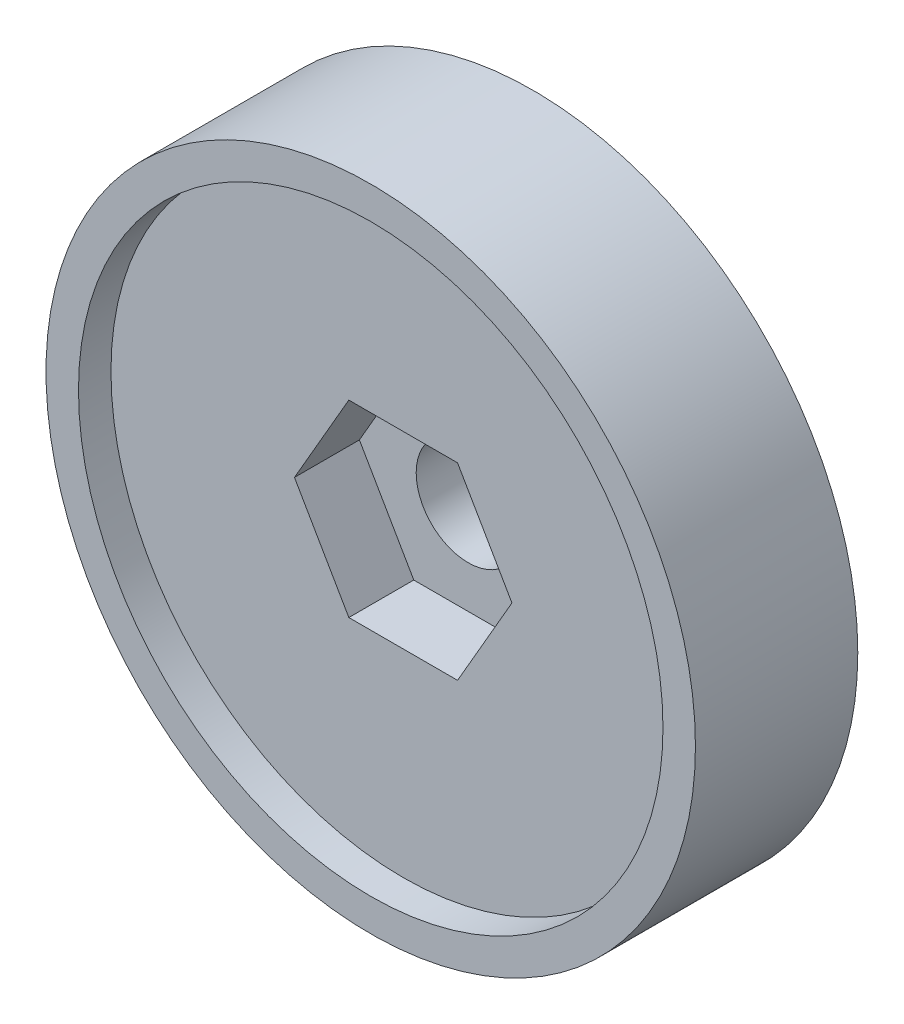
SolidWorks part; units mm, degrees
ref_plane "Front Plane" through (0, 0, 0) normal (0, 0, 1) x (1, 0, 0)
ref_plane "Top Plane" through (0, 0, 0) normal (0, 1, 0) x (1, 0, 0)
ref_plane "Right Plane" through (0, 0, 0) normal (1, 0, 0) x (0, 0, -1)
sketch "Sketch1" plane through (0, 0, 0) normal (0, 0, 1) x (1, 0, 0)
  circle A0 centre (-85, 80) radius 10
  circle A1 centre (-85, 80) radius 1.5 construction
  circle A2 centre (-85, 80) radius 1.5
  dimension "D1" = 20
extrude "Boss-Extrude1" add sketch "Sketch1" along normal blind 2
sketch "Sketch2" plane through (0, 0, 2) normal (0, 0, 1) x (1, 0, 0)
  circle A0 centre (-85, 80) radius 10
  circle A1 centre (-85, 80) radius 1.5 construction
  circle A2 centre (-85, 80) radius 1.5
  circle M3 centre (-85, 80) radius 1.5
  dimension "D1" = 20
extrude "Boss-Extrude2" add sketch "Sketch2" along normal blind 3 contours A0 M3 | M3
sketch "Sketch3" plane through (0, 0, 0) normal (0, 0, -1) x (-1, 0, 0)
  circle A0 centre (85, 80) radius 1.6
  dimension "D1" = 3.2
extrude "Cut-Extrude1" cut sketch "Sketch3" against normal through all
sketch "Sketch4" plane through (0, 0, 5) normal (0, 0, 1) x (1, 0, 0)
  line L1 (-88.3486, 80) -> (-86.6743, 77.1)
  line L2 (-86.6743, 77.1) -> (-83.3257, 77.1)
  line L3 (-83.3257, 77.1) -> (-81.6514, 80)
  line L4 (-81.6514, 80) -> (-83.3257, 82.9)
  line L5 (-83.3257, 82.9) -> (-86.6743, 82.9)
  line L6 (-86.6743, 82.9) -> (-88.3486, 80)
  circle A0 centre (-85, 80) radius 2.9 construction
  dimension "D1" = 5.8
extrude "Cut-Extrude2" cut sketch "Sketch4" against normal offset from surface (3 mm away) 2 up to face at (-86.6, 80, 0)
sketch "Sketch5" plane through (0, 0, 5) normal (0, 0, 1) x (1, 0, 0)
  circle A0 centre (-85, 80) radius 9
  circle A1 centre (-85, 80) radius 10 construction
  dimension "D1" = 18
extrude "Cut-Extrude3" cut sketch "Sketch5" against normal blind 1
